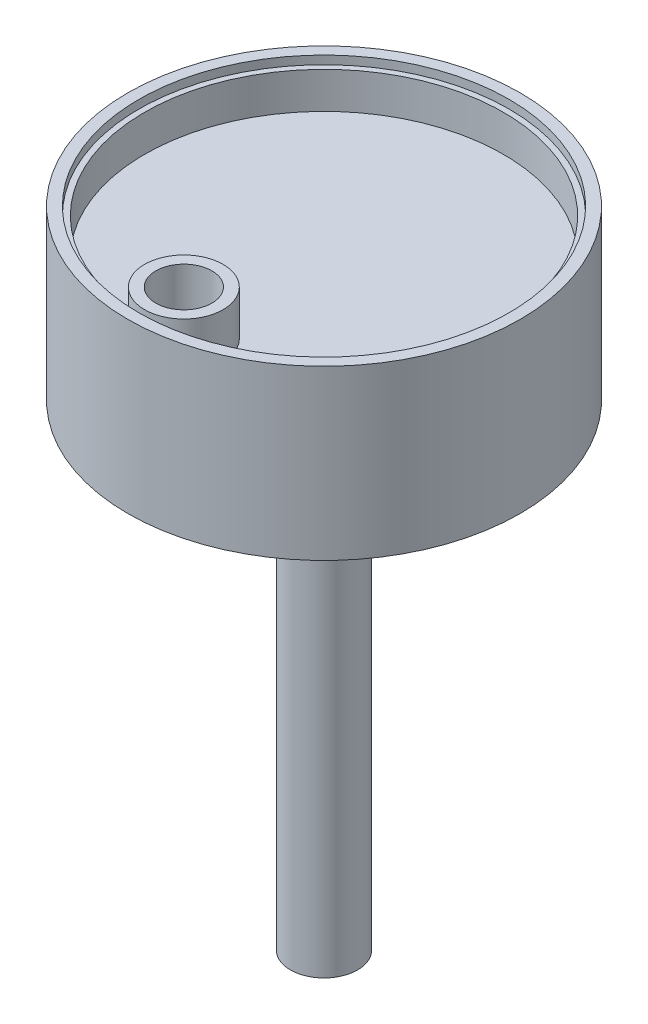
SolidWorks part; units mm, degrees
ref_plane "Front Plane" through (0, 0, 0) normal (0, 0, 1) x (1, 0, 0)
ref_plane "Top Plane" through (0, 0, 0) normal (0, 1, 0) x (1, 0, 0)
ref_plane "Right Plane" through (0, 0, 0) normal (1, 0, 0) x (0, 0, -1)
sketch "Sketch2" plane through (0, 0, 0) normal (0, 1, 0) x (1, 0, 0)
  circle A0 centre (0, 0) radius 35
  dimension "D1" = 70
extrude "Boss-Extrude2" add sketch "Sketch2" along normal blind 20
sketch "Sketch3" plane through (0, 0, 0) normal (0, -1, 0) x (1, 0, 0)
  circle A0 centre (0, 0) radius 32
  dimension "D1" = 64
extrude "Cut-Extrude1" cut sketch "Sketch3" against normal blind 15
sketch "Sketch4" plane through (0, 15, 0) normal (0, -1, 0) x (1, 0, 0)
  circle A0 centre (0, 0) radius 6
  dimension "D1" = 12
extrude "Boss-Extrude3" add sketch "Sketch4" along normal blind 100
sketch "Sketch6" plane through (0, 20, 0) normal (0, 1, 0) x (1, 0, 0)
  circle A0 centre (0, 0) radius 4
  dimension "D1" = 8
extrude "Cut-Extrude3" cut sketch "Sketch6" against normal blind 95
sketch "Sketch8" plane through (0, 20, 0) normal (0, 1, 0) x (1, 0, 0)
  circle A0 centre (0, 0) radius 35
extrude "Boss-Extrude4" add sketch "Sketch8" along normal blind 10
sketch "Sketch9" plane through (0, 30, 0) normal (0, 1, 0) x (1, 0, 0)
  circle A0 centre (0, 0) radius 32
  dimension "D1" = 64
extrude "Cut-Extrude4" cut sketch "Sketch9" against normal blind 8
sketch "Sketch10" plane through (0, 30, 0) normal (0, 1, 0) x (1, 0, 0)
  circle A0 centre (0, 0) radius 33
  circle A1 centre (0, 0) radius 31
  dimension "D1" = 66
  dimension "D2" = 62
extrude "Cut-Extrude5" cut sketch "Sketch10" against normal blind 1.5
sketch "Sketch11" plane through (0, 22, 0) normal (0, 1, 0) x (1, 0, 0)
  circle A1 centre (0, -25) radius 5
  point P4 (0, 0)
  dimension "D3" = 10
  dimension "D2" = 25
extrude "Cut-Extrude6" cut sketch "Sketch11" against normal through all
sketch "Sketch13" plane through (0, 22, 0) normal (0, 1, 0) x (1, 0, 0)
  circle A0 centre (0, -25) radius 5 construction
  circle A1 centre (0, -25) radius 5
  circle A2 centre (0, -25) radius 7
  dimension "D1" = 14
extrude "Boss-Extrude16" add sketch "Sketch13" along normal blind 8 separate body
